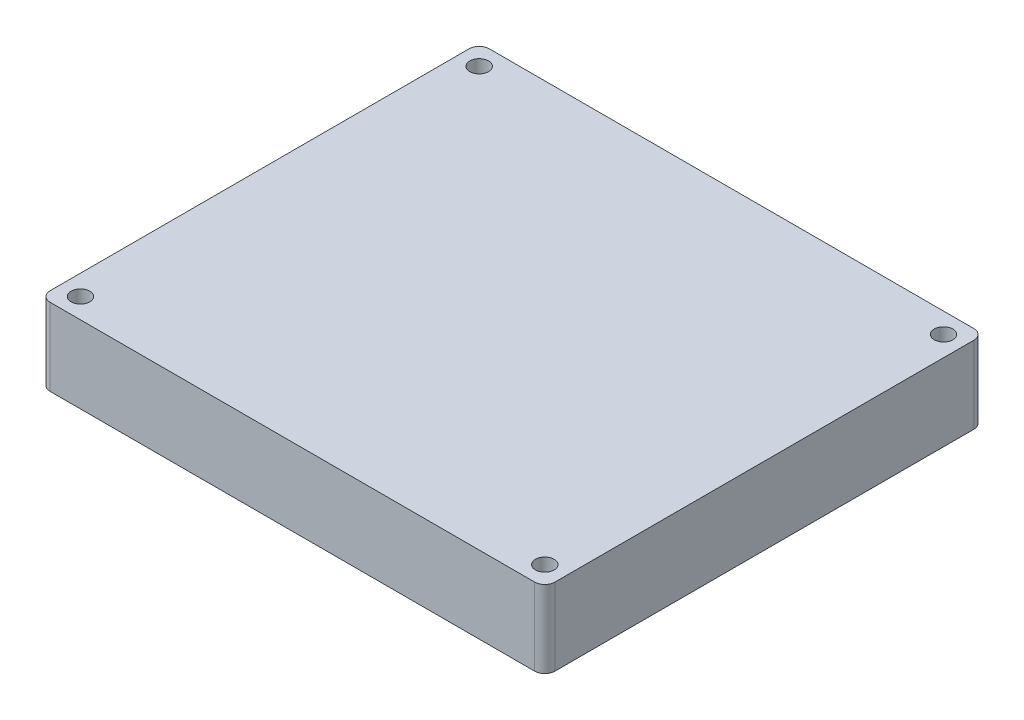
SolidWorks part; units mm, degrees
material "1060 Alloy"
ref_plane "Front Plane" through (0, 0, 0) normal (0, 0, 1) x (1, 0, 0)
ref_plane "Top Plane" through (0, 0, 0) normal (0, 1, 0) x (1, 0, 0)
ref_plane "Right Plane" through (0, 0, 0) normal (1, 0, 0) x (0, 0, -1)
sketch "Sketch1" plane through (0, 0, 0) normal (0, 1, 0) x (1, 0, 0)
  line L0 (-50, 0) -> (50, 0) construction
  line L1 (-48, -43.5) -> (48, -43.5)
  line L2 (-50, -41.5) -> (-50, 41.5)
  line L3 (-48, 43.5) -> (48, 43.5)
  line L4 (50, -41.5) -> (50, 41.5)
  line L5 (-50, -43.5) -> (50, 43.5) construction
  line L6 (-50, 43.5) -> (50, -43.5) construction
  line L7 (0, 43.5) -> (0, -43.5) construction
  circle A0 centre (46, 39.5) radius 1.85
  circle A1 centre (46, -39.5) radius 1.85
  circle A2 centre (-46, -39.5) radius 1.85
  circle A3 centre (-46, 39.5) radius 1.85
  arc A4 (-48, -43.5) -> (-50, -41.5) centre (-48, -41.5) cw
  arc A5 (48, -43.5) -> (50, -41.5) centre (48, -41.5) ccw
  arc A6 (48, 43.5) -> (50, 41.5) centre (48, 41.5) cw
  arc A7 (-50, 41.5) -> (-48, 43.5) centre (-48, 41.5) cw
  point P0 (0, 0)
  dimension "D3" = 3.7
  dimension "D4" = 79
  dimension "D5" = 92
  dimension "D6" = 2
  dimension "D1" = 87
  dimension "D2" = 100
extrude "Boss-Extrude1" add sketch "Sketch1" along normal blind 15.29
